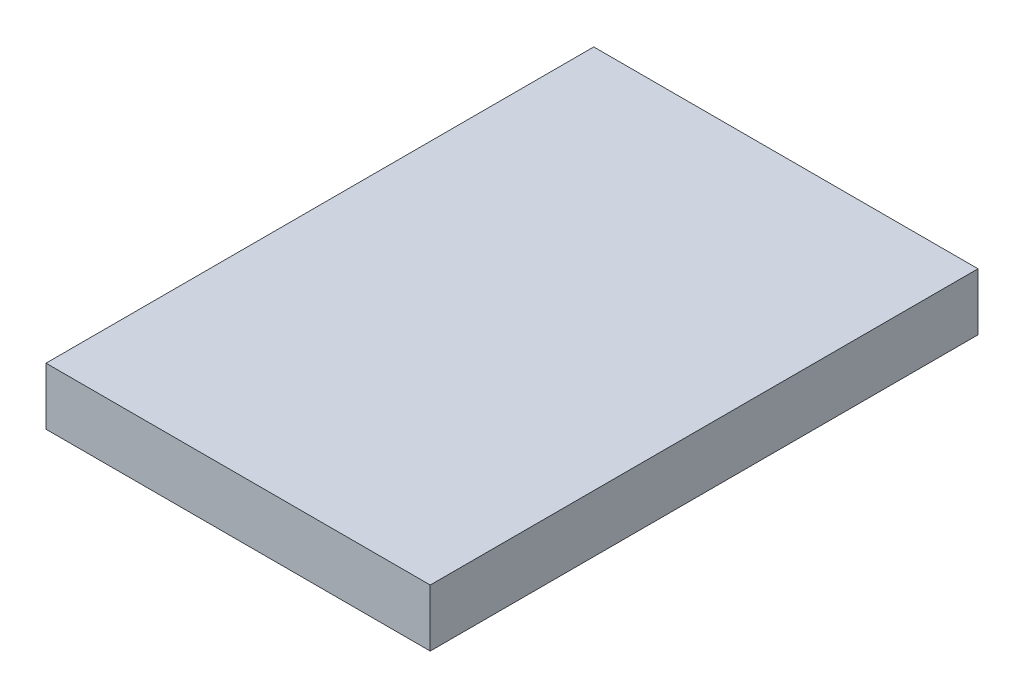
SolidWorks part; units mm, degrees
ref_plane "Front Plane" through (0, 0, 0) normal (0, 0, 1) x (1, 0, 0)
ref_plane "Top Plane" through (0, 0, 0) normal (0, 1, 0) x (1, 0, 0)
ref_plane "Right Plane" through (0, 0, 0) normal (1, 0, 0) x (0, 0, -1)
sketch "Sketch1" plane through (0, 0, 0) normal (0, 1, 0) x (1, 0, 0)
  line L1 (0, 0) -> (74.6125, 0)
  line L2 (0, 0) -> (0, 106.3625)
  line L3 (0, 106.3625) -> (74.6125, 106.3625)
  line L4 (74.6125, 0) -> (74.6125, 106.3625)
  dimension "D1" = 74.6125
  dimension "D2" = 106.3625
extrude "Boss-Extrude1" add sketch "Sketch1" along normal blind 11.1125
